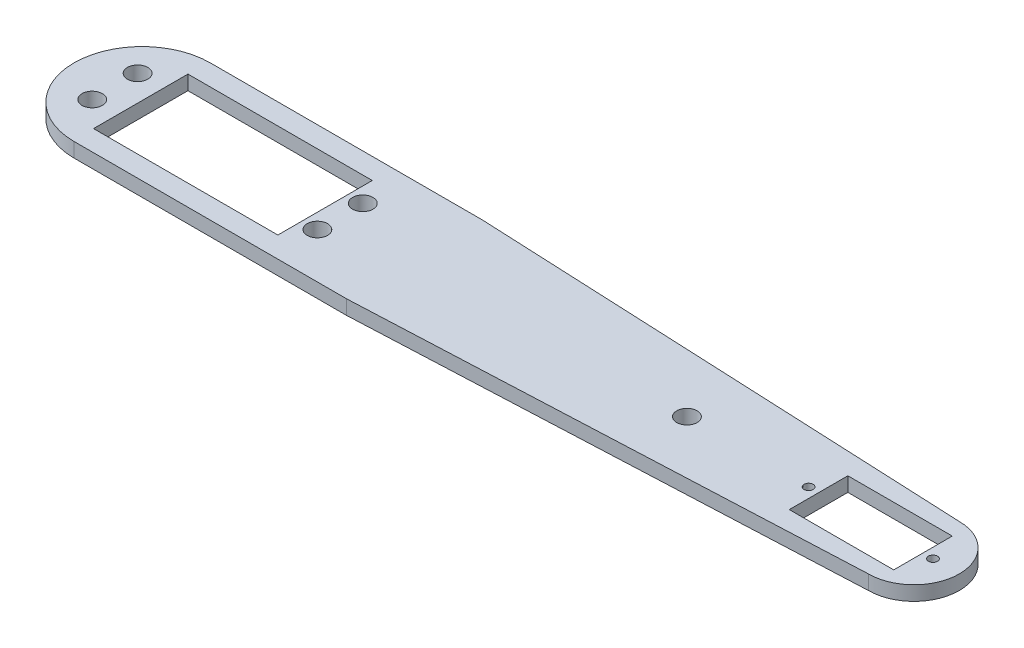
SolidWorks part; units mm, degrees
ref_plane "Front Plane" through (0, 0, 0) normal (0, 0, 1) x (1, 0, 0)
ref_plane "Top Plane" through (0, 0, 0) normal (0, 1, 0) x (1, 0, 0)
ref_plane "Right Plane" through (0, 0, 0) normal (1, 0, 0) x (0, 0, -1)
sketch "Sketch1" plane through (0, 0, 0) normal (0, 1, 0) x (1, 0, 0)
  line L0 (-162.3874, 17.2447) -> (-102.3874, 17.2447)
  line L1 (-102.3874, 17.2447) -> (7.6126, 12.2447)
  line L2 (-162.3874, -12.7553) -> (-102.3874, -12.7553)
  line L3 (-102.3874, -12.7553) -> (7.6126, -7.7553)
  line L4 (-168.3874, 19.311) -> (-168.3874, -13.0468) construction
  line L5 (-15.5874, 2.2447) -> (11.8126, 2.2447) construction
  line L6 (-162.6926, -8.1553) -> (-122.0926, -8.1553)
  line L7 (-162.6926, -8.1553) -> (-162.6926, 12.6447)
  line L8 (-162.6926, 12.6447) -> (-122.0926, 12.6447)
  line L9 (-122.0926, -8.1553) -> (-122.0926, 12.6447)
  line L10 (-13.3874, 8.6947) -> (9.6126, 8.6947)
  line L11 (-13.3874, 8.6947) -> (-13.3874, -4.2053)
  line L12 (-13.3874, -4.2053) -> (9.6126, -4.2053)
  line L13 (9.6126, 8.6947) -> (9.6126, -4.2053)
  line L14 (-13.3874, 8.6947) -> (9.6126, -4.2053) construction
  line L15 (-13.3874, -4.2053) -> (9.6126, 8.6947) construction
  arc A0 (-162.3874, 17.2447) -> (-162.3874, -12.7553) centre (-162.3874, 2.2447) ccw
  arc A1 (7.6126, -7.7553) -> (7.6126, 12.2447) centre (7.6126, 2.2447) ccw
  circle A3 centre (-168.3874, 7.2447) radius 2.25
  circle A4 centre (-168.3874, -2.7553) radius 2.25
  circle A5 centre (-118.7874, 7.2447) radius 2.25
  circle A6 centre (-118.7874, -2.7553) radius 2.25
  circle A7 centre (-15.5874, 2.2447) radius 1
  circle A8 centre (11.8126, 2.2447) radius 1
  circle A9 centre (-42.3874, 2.2447) radius 2.25
  point P20 (-1.8874, 2.2447)
  dimension "D6" = 4.5
  dimension "D17" = 2
  dimension "D18" = 4.5
  dimension "D2" = 30
  dimension "D3" = 20
  dimension "D4" = 5
  dimension "D5" = 5
  dimension "D7" = 49.6
  dimension "D8" = 60
  dimension "D9" = 170
  dimension "D10" = 6
  dimension "D11" = 0
  dimension "D12" = 20.8
  dimension "D13" = 40.6
  dimension "D14" = 12.9
  dimension "D15" = 23
  dimension "D16" = 27.4
  dimension "D19" = 0.3053
  dimension "D20" = 2
  dimension "D21" = 50
extrude "Boss-Extrude1" add sketch "Sketch1" along normal blind 3.175
equation "\"D5@Sketch1\"=\"D4@Sketch1\""
